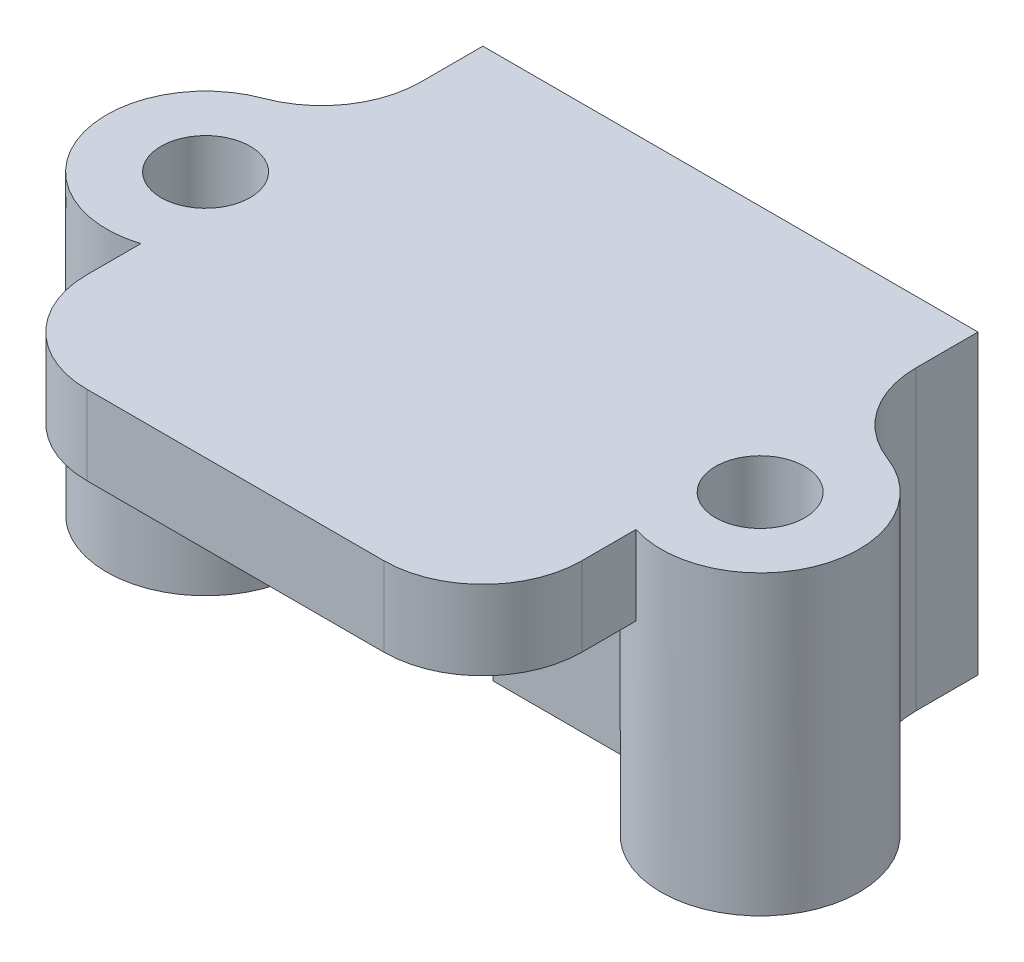
SolidWorks part; units mm, degrees
ref_plane "Front Plane" through (0, 0, 0) normal (0, 0, 1) x (1, 0, 0)
ref_plane "Top Plane" through (0, 0, 0) normal (0, 1, 0) x (1, 0, 0)
ref_plane "Right Plane" through (0, 0, 0) normal (1, 0, 0) x (0, 0, -1)
sketch "Sketch6" plane through (0, 0, 0) normal (0, -1, 0) x (1, 0, 0)
  line L1 (-12.5, -12.5) -> (12.5, -12.5)
  line L2 (-12.5, -12.5) -> (-12.5, 12.5)
  line L3 (-12.5, 12.5) -> (12.5, 12.5)
  line L4 (12.5, -12.5) -> (12.5, 12.5)
  line L5 (-12.5, -12.5) -> (12.5, 12.5) construction
  line L6 (-12.5, 12.5) -> (12.5, -12.5) construction
  point P0 (0, 0)
  dimension "D1" = 25
  dimension "D2" = 25
extrude "Boss-Extrude3" add sketch "Sketch6" along normal blind 4
sketch "Sketch11" plane through (0, 0, 0) normal (0, 1, 0) x (1, 0, 0)
  line L0 (-1000, 0) -> (49000, 0) construction
  line L1 (-12.5, 12.5) -> (12.5, 12.5) construction
  line L2 (0, -1000) -> (0, 49000) construction
  circle A0 centre (-14, 0) radius 5
  circle A1 centre (14, 0) radius 5
  dimension "D2" = 14
  dimension "D3" = 10
  dimension "D4" = 10
  dimension "D1" = 28
  dimension "D5" = 12.5
extrude "Boss-Extrude7" add sketch "Sketch11" against normal blind 15
sketch "Sketch8" plane through (0, -4, 0) normal (0, -1, 0) x (1, 0, 0)
  line L0 (-12.5, 0) -> (12.5, 0)
  line L1 (-12.5, 12.5) -> (-12.5, 4.7697) construction
  line L2 (-12.5, 0) -> (-12.5, -12.5)
  line L3 (-12.5, -12.5) -> (12.5, -12.5)
  line L4 (12.5, -12.5) -> (12.5, 0)
extrude "Boss-Extrude5" add sketch "Sketch8" along normal blind 11
sketch "Sketch12" plane through (0, 0, 0) normal (0, 1, 0) x (1, 0, 0)
  circle A0 centre (-14, 0) radius 2.25
  circle A1 centre (14, 0) radius 2.25
  dimension "D1" = 4.5
  dimension "D2" = 4.5
extrude "Cut-Extrude3" cut sketch "Sketch12" against normal through all
sketch "Sketch9" plane through (0, -15, 0) normal (0, -1, 0) x (1, 0, 0)
  line L0 (9, 0) -> (-9, 0) construction
  line L1 (-0.5, 0) -> (0.5, 0)
  line L2 (-0.5, 0) -> (-0.5, -7)
  line L3 (-0.5, -7) -> (0.5, -7)
  line L4 (0.5, 0) -> (0.5, -7)
  dimension "D1" = 7
  dimension "D2" = 1
extrude "Cut-Extrude2" cut sketch "Sketch9" against normal up to surface (11 mm away) up to face at (0, -4, 5.9476)
sketch "Sketch13" plane through (0, -4, 0) normal (0, -1, 0) x (1, 0, 0)
  line L0 (-11, 0) -> (-11, 12.5)
  line L1 (12.5, 12.5) -> (-12.5, 12.5) construction
  line L2 (-11, 12.5) -> (11, 12.5)
  line L3 (11, 12.5) -> (11, 0)
  arc A0 (-11, 0) -> (11, 0) centre (0, 0) ccw
  dimension "D1" = 22
extrude "Cut-Extrude4" cut sketch "Sketch13" along normal blind 1.5
fillet "Fillet2" radius 5 4 edges at (12.5, -7.5, -4.7697) (-12.5, -7.5, -4.7697) (12.5, -2, 12.5) (-12.5, -2, 12.5)
